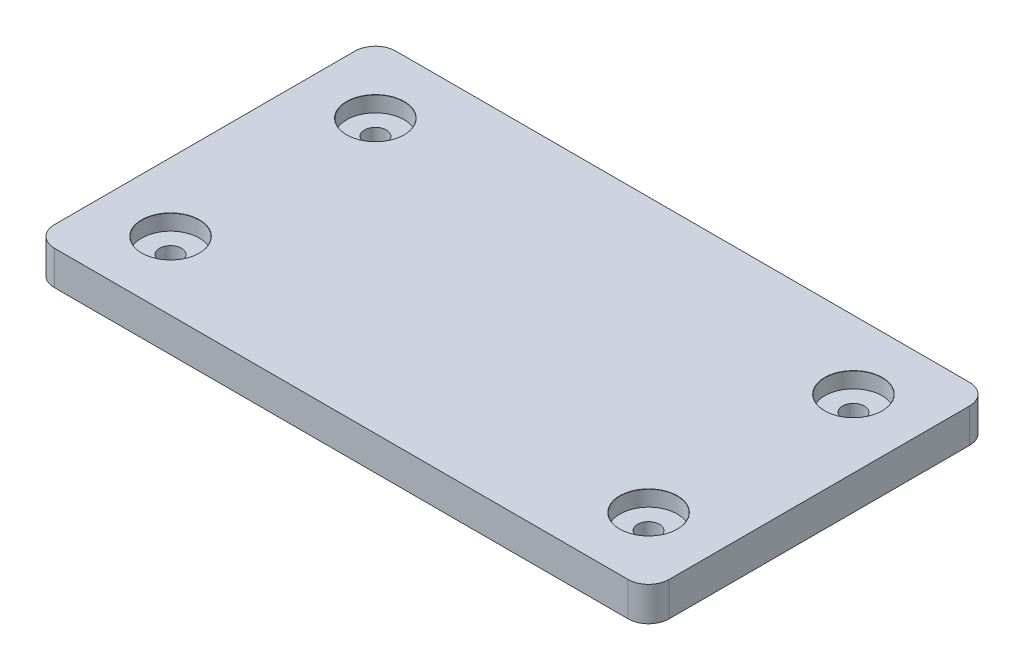
SolidWorks part; units mm, degrees
ref_plane "Front Plane" through (0, 0, 0) normal (0, 0, 1) x (1, 0, 0)
ref_plane "Top Plane" through (0, 0, 0) normal (0, 1, 0) x (1, 0, 0)
ref_plane "Right Plane" through (0, 0, 0) normal (1, 0, 0) x (0, 0, -1)
sketch "Sketch1" plane through (0, 0, 0) normal (0, 1, 0) x (1, 0, 0)
  line L7 (45, -25) -> (-45, -25)
  line L8 (45, -25) -> (45, 25)
  line L9 (45, 25) -> (-45, 25)
  line L10 (-45, -25) -> (-45, 25)
  point P0 (0, 0)
  point P7 (0, 0)
extrude "Boss-Extrude2" add sketch "Sketch1" along normal blind 5
fillet "Fillet1" radius 3 4 edges at (45, 2.5, -25) (45, 2.5, 25) (-45, 2.5, 25) (-45, 2.5, -25)
sketch "Sketch5" plane through (0, 5, 0) normal (0, 1, 0) x (1, 0, 0)
  line L1 (-35, -15) -> (35, -15) construction
  line L2 (-35, -15) -> (-35, 15) construction
  line L3 (-35, 15) -> (35, 15) construction
  line L4 (35, -15) -> (35, 15) construction
  line L5 (-35, -15) -> (35, 15) construction
  line L6 (-35, 15) -> (35, -15) construction
  point P0 (0, 0)
  dimension "D1" = 70
  dimension "D2" = 30
hole_wizard "CBORE for M3 Hex Head Machine Screw1" positions "3DSketch1" profile "Sketch6" counterbore size "M3" standard "ANSI Metric"
sketch3d "3DSketch1"
  point P0 (-35, 5, -15)
  point P3 (-35, 5, 15)
  point P6 (35, 5, 15)
  point P9 (35, 5, -15)
sketch "Sketch6" plane through (-35, 5, -15) normal (1, 0, 0) x (0, 0, 1)
  line L0 (0, 0) -> (0, 5.9614)
  line L1 (0, 5.9614) -> (1.6, 5)
  line L2 (1.6, 5) -> (1.6, 2.3)
  line L3 (1.6, 2.3) -> (4.2, 2.3)
  line L5 (4.2, 2.3) -> (4.2, 0.025)
  line L6 (4.2, 0.025) -> (4.225, 0)
  line L7 (4.225, 0) -> (0, 0)
  line L8 (-4.2, 0.025) -> (-4.225, 0) construction
  line L10 (0, 5.9614) -> (-1.6, 5) construction
  line L11 (0, -6.35) -> (0, 107.95) construction
  dimension "Hole Dia." = 3.2
  dimension "Hole Depth" = 5
  dimension "C'Bore Dia." = 8.4
  dimension "C'Bore Depth" = 2.3
  dimension "Near C'Sink Dia." = 8.45
  dimension "Near C'Sink Angle" = 90
  dimension "Drill Angle" = 118
